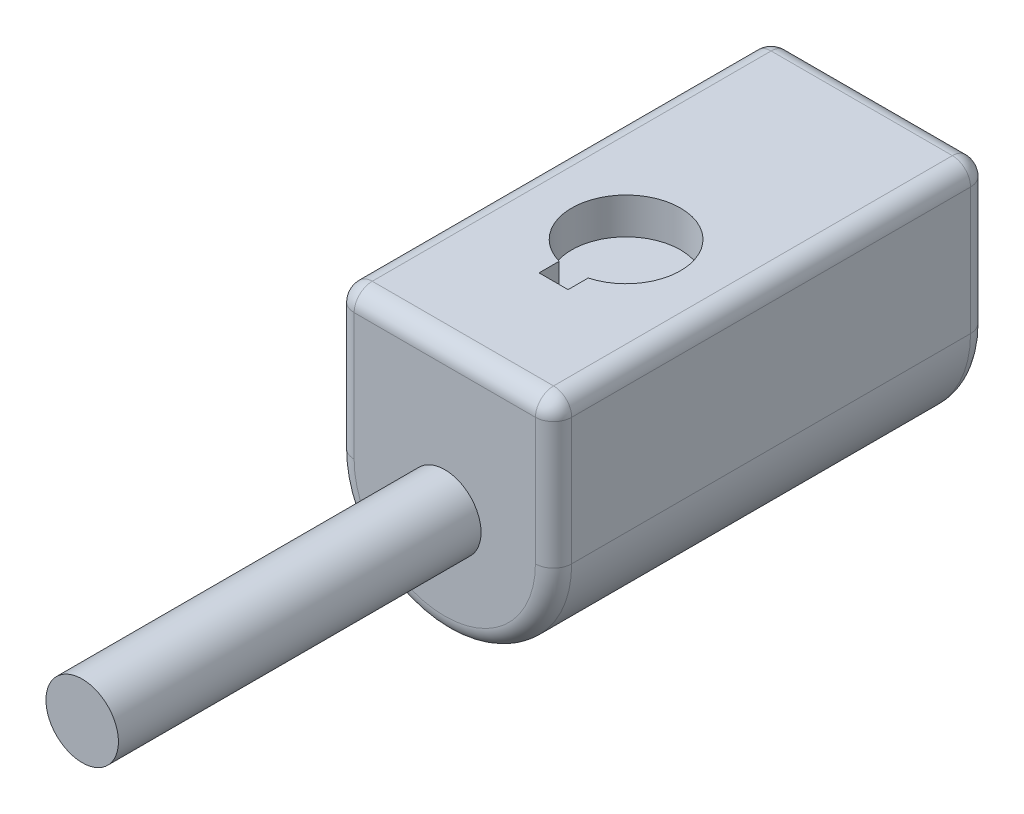
SolidWorks part; units mm, degrees
ref_plane "Front Plane" through (0, 0, 0) normal (0, 0, 1) x (1, 0, 0)
ref_plane "Top Plane" through (0, 0, 0) normal (0, 1, 0) x (1, 0, 0)
ref_plane "Right Plane" through (0, 0, 0) normal (1, 0, 0) x (0, 0, -1)
sketch "Sketch1" plane through (0, 0, 0) normal (0, 0, 1) x (1, 0, 0)
  line L2 (-38.1, 0) -> (-38.1, 50.8)
  line L3 (-38.1, 50.8) -> (38.1, 50.8)
  line L4 (38.1, 0) -> (38.1, 50.8)
  arc A0 (-38.1, 0) -> (38.1, 0) centre (0, 0) ccw
  dimension "D1" = 76.2
  dimension "D2" = 76.2
  dimension "D3" = 50.8
extrude "Boss-Extrude1" add sketch "Sketch1" against normal blind 152.4
sketch "Sketch2" plane through (0, 0, 0) normal (0, 0, 1) x (1, 0, 0)
  circle A0 centre (0, 0) radius 12.7
  dimension "D1" = 25.4
extrude "Boss-Extrude2" add sketch "Sketch2" along normal blind 127
sketch "Sketch3" plane through (0, 50.8, 0) normal (0, 1, 0) x (1, 0, 0)
  line L0 (38.1, 0) -> (-38.1, 0) construction
  line L1 (38.1, 152.4) -> (38.1, 0) construction
  line L4 (5.08, 45.1398) -> (5.08, 38.1)
  line L5 (5.08, 38.1) -> (-5.08, 38.1)
  line L6 (-5.08, 45.1398) -> (-5.08, 38.1)
  arc A0 (5.08, 45.1398) -> (-5.08, 45.1398) centre (0, 63.5) ccw
  dimension "D1" = 38.1
  dimension "D2" = 63.5
  dimension "D3" = 38.1
  dimension "D4" = 25.4
  dimension "D5" = 5.08
  dimension "D6" = 10.16
extrude "Cut-Extrude1" cut sketch "Sketch3" against normal blind 12.7
fillet "Fillet1" radius 6.35 10 edges at (-38.1, 25.4, 0) (0, -38.1, 0) (-38.1, 25.4, -152.4) (0, -38.1, -152.4) (-38.1, 50.8, -76.2) (0, 50.8, -152.4) (38.1, 50.8, -76.2) (0, 50.8, 0) (38.1, 25.4, 0) (38.1, 25.4, -152.4)
